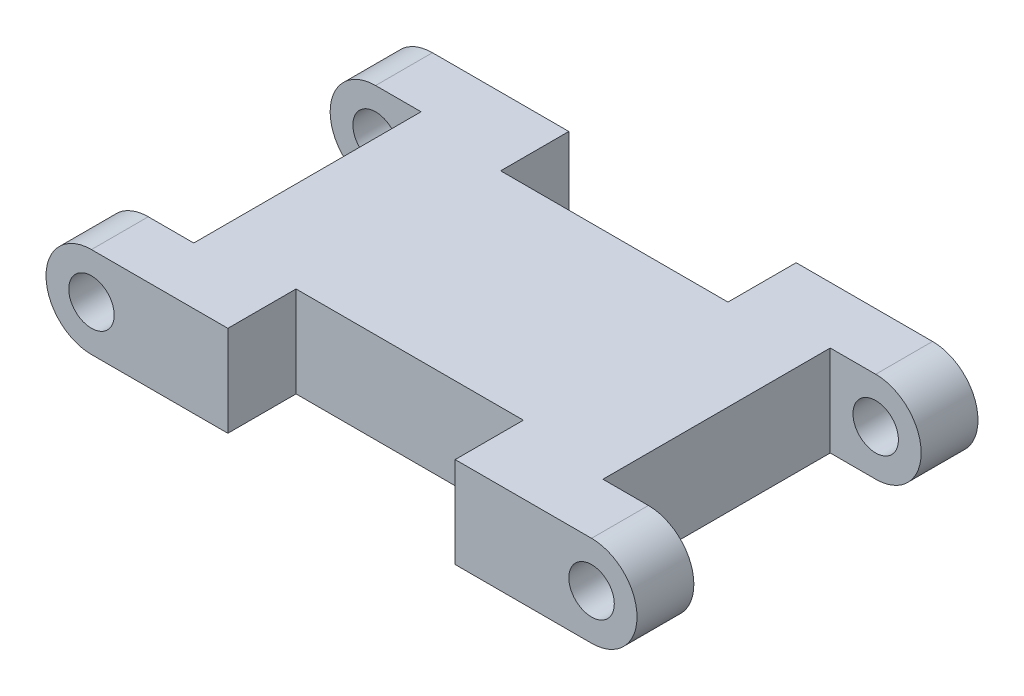
SolidWorks part; units mm, degrees
material "6061 Alloy"
ref_plane "Front Plane" through (0, 0, 0) normal (0, 0, 1) x (1, 0, 0)
ref_plane "Top Plane" through (0, 0, 0) normal (0, 1, 0) x (1, 0, 0)
ref_plane "Right Plane" through (0, 0, 0) normal (1, 0, 0) x (0, 0, -1)
sketch "Sketch1" plane through (0, 0, 0) normal (0, 0, 1) x (1, 0, 0)
  line L2 (0, 0) -> (0, 16.9196) construction
  line L5 (-11, 4) -> (11, 4)
  line L6 (-11, 0) -> (11, 0)
  circle A2 centre (-11, 2) radius 1
  circle A3 centre (11, 2) radius 1
  arc A4 (11, 0) -> (11, 4) centre (11, 2) ccw
  arc A5 (-11, 4) -> (-11, 0) centre (-11, 2) ccw
  dimension "D1" = 4
  dimension "D2" = 2
  dimension "D4" = 22
extrude "Boss-Extrude1" add sketch "Sketch1" along normal mid plane 15
sketch "Sketch2" plane through (0, 4, 0) normal (0, 1, 0) x (1, 0, 0)
  line L0 (-13, 5) -> (-9, 5)
  line L2 (-9, 5) -> (-9, -5)
  line L3 (0, 0) -> (-20.4365, 0) construction
  line L4 (-9, -5) -> (-13, -5)
  line L5 (-13, -5) -> (-13, 5)
  line L6 (0, 0) -> (0, 17.703) construction
  line L7 (-5, 7.5) -> (-5, 4.5)
  line L8 (11, 7.5) -> (-11, 7.5) construction
  line L9 (-5, 4.5) -> (5, 4.5)
  line L10 (5, 4.5) -> (5, 7.5)
  line L11 (5, 7.5) -> (-5, 7.5)
  line L12 (5, -4.5) -> (5, -7.5)
  line L13 (-5, -4.5) -> (5, -4.5)
  line L14 (-5, -7.5) -> (-5, -4.5)
  line L15 (5, -7.5) -> (-5, -7.5)
  line L16 (9, -5) -> (13, -5)
  line L17 (9, 5) -> (9, -5)
  line L18 (13, 5) -> (9, 5)
  line L19 (13, -5) -> (13, 5)
  line L21 (-13, 7.5) -> (-13, -7.5) construction
  dimension "D1" = 10
  dimension "D2" = 4
  dimension "D3" = 10
  dimension "D4" = 3
extrude "Cut-Extrude1" cut sketch "Sketch2" against normal up to next
